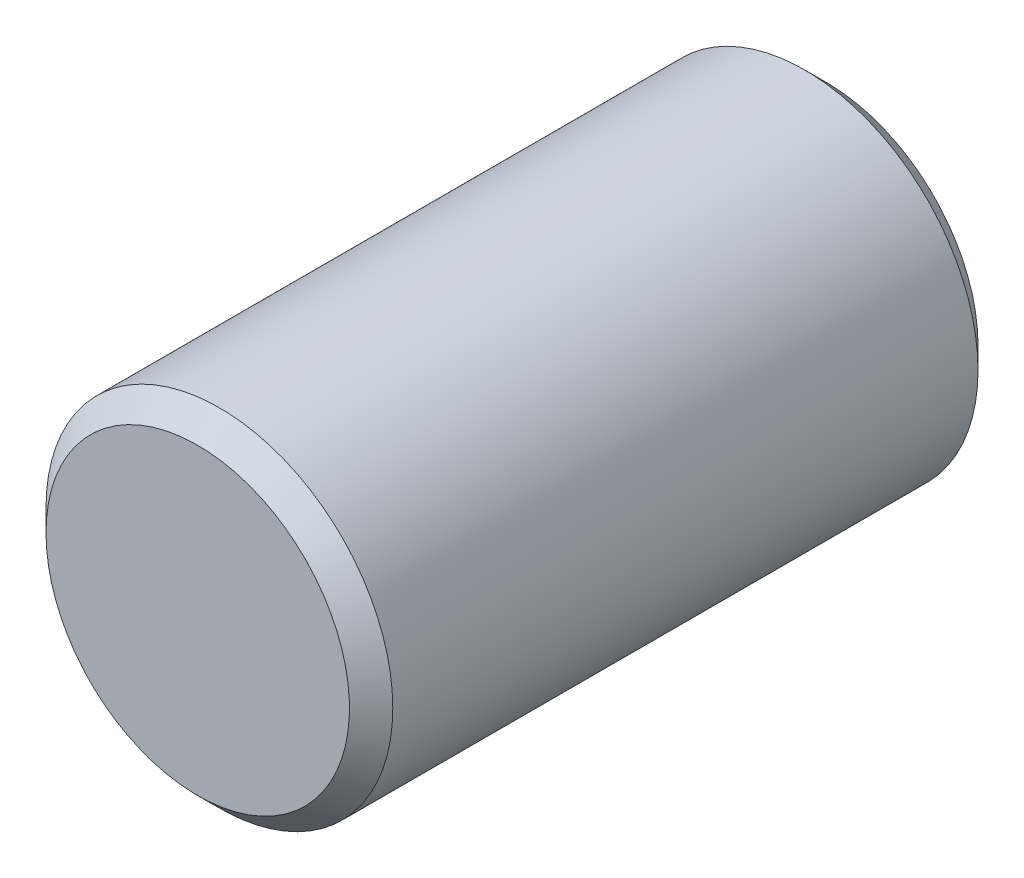
SolidWorks part; units mm, degrees
ref_plane "Front Plane" through (0, 0, 0) normal (0, 0, 1) x (1, 0, 0)
ref_plane "Top Plane" through (0, 0, 0) normal (0, 1, 0) x (1, 0, 0)
ref_plane "Right Plane" through (0, 0, 0) normal (1, 0, 0) x (0, 0, -1)
sketch "Sketch1" plane through (0, 0, 0) normal (1, 0, 0) x (0, 0, -1)
  line L1 (0, 0) -> (14.5, 0)
  line L2 (0, 0) -> (0, 4)
  line L3 (0, 4) -> (14.5, 4)
  line L4 (14.5, 0) -> (14.5, 4)
  line L5 (0, 0) -> (14.5, 4) construction
  line L6 (0, 4) -> (14.5, 0) construction
  point P4 (7.25, 2)
  dimension "D1" = 14.5
  dimension "D2" = 4
revolve "Revolve1" add sketch "Sketch1" angle 360 about L1
chamfer "Chamfer1" distance 0.5 angle 45 2 edges at (4, 0, -14.5) (4, 0, 0)
